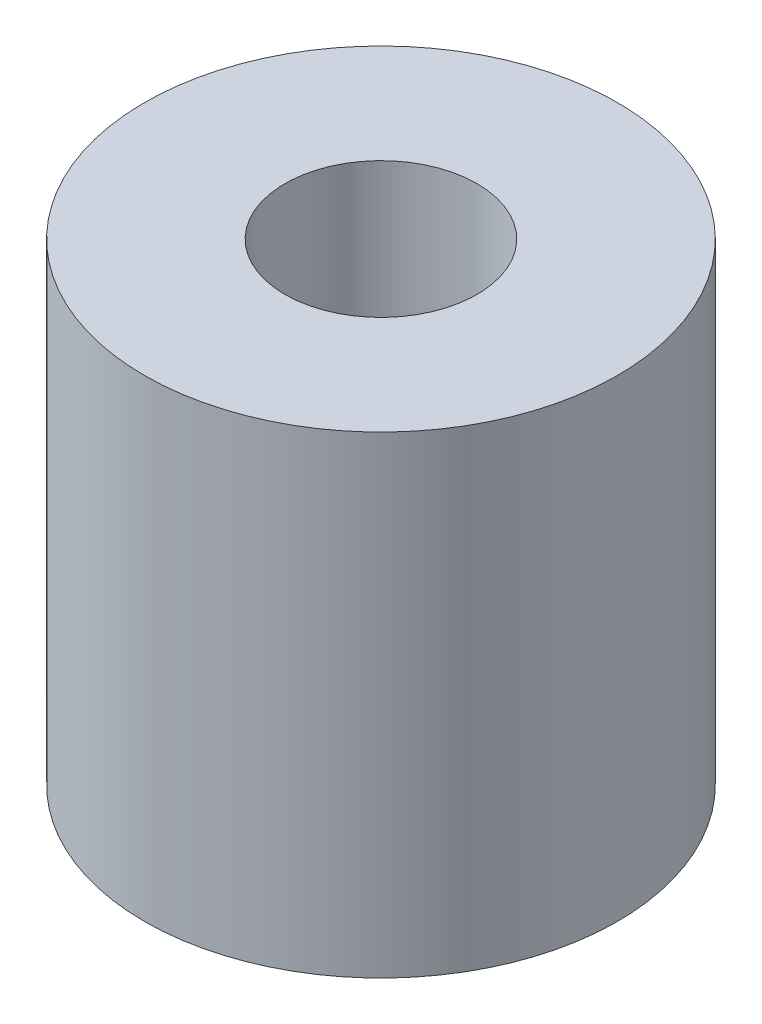
SolidWorks part; units mm, degrees
material "Nylon 101"
ref_plane "Front Plane" through (0, 0, 0) normal (0, 0, 1) x (1, 0, 0)
ref_plane "Top Plane" through (0, 0, 0) normal (0, 1, 0) x (1, 0, 0)
ref_plane "Right Plane" through (0, 0, 0) normal (1, 0, 0) x (0, 0, -1)
sketch "Sketch1" plane through (0, 0, 0) normal (0, 1, 0) x (1, 0, 0)
  circle A0 centre (0, 0) radius 1.625
  circle A1 centre (0, 0) radius 4
  dimension "D1" = 3.25
  dimension "D2" = 8
extrude "Boss-Extrude1" add sketch "Sketch1" along normal mid plane 8
